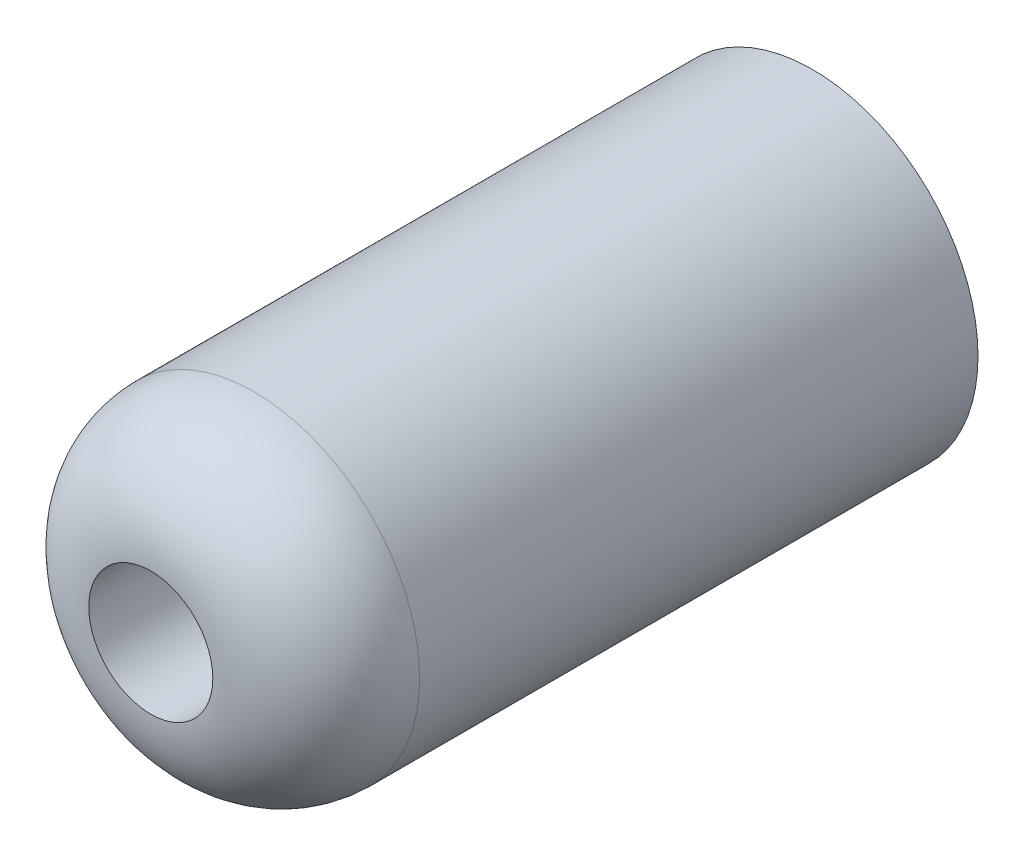
SolidWorks part; units mm, degrees
material "Glass"
ref_plane "Front Plane" through (0, 0, 0) normal (1, 0, 0) x (0, 1, 0)
ref_plane "Top Plane" through (0, 0, 0) normal (0, 0, 1) x (0, 1, 0)
ref_plane "Right Plane" through (0, 0, 0) normal (0, 1, 0) x (-1, 0, 0)
sketch "Sketch1" plane through (0, 0, 0) normal (1, 0, 0) x (0, 1, 0)
  line L0 (0, 20.7874) -> (0, -16.126) construction
  line L1 (-15.8926, 0) -> (18.7531, 0) construction
  line L2 (0, 16) -> (3, 16)
  line L3 (8, 11) -> (8, -16)
  line L4 (8, -16) -> (6, -16)
  line L6 (6, 11) -> (6, -16)
  line L7 (0, 11) -> (8, 11)
  line L8 (3, 16) -> (3, 11)
  line L9 (0, 16) -> (0, 11)
  arc A0 (3, 16) -> (8, 11) centre (3, 11) cw
  point P15 (8, 16)
  dimension "D5" = 5
  dimension "D1" = 32
  dimension "D2" = 16
  dimension "D3" = 2
  dimension "D4" = 16
revolve "Revolve1" add sketch "Sketch1" angle 360 about L0
